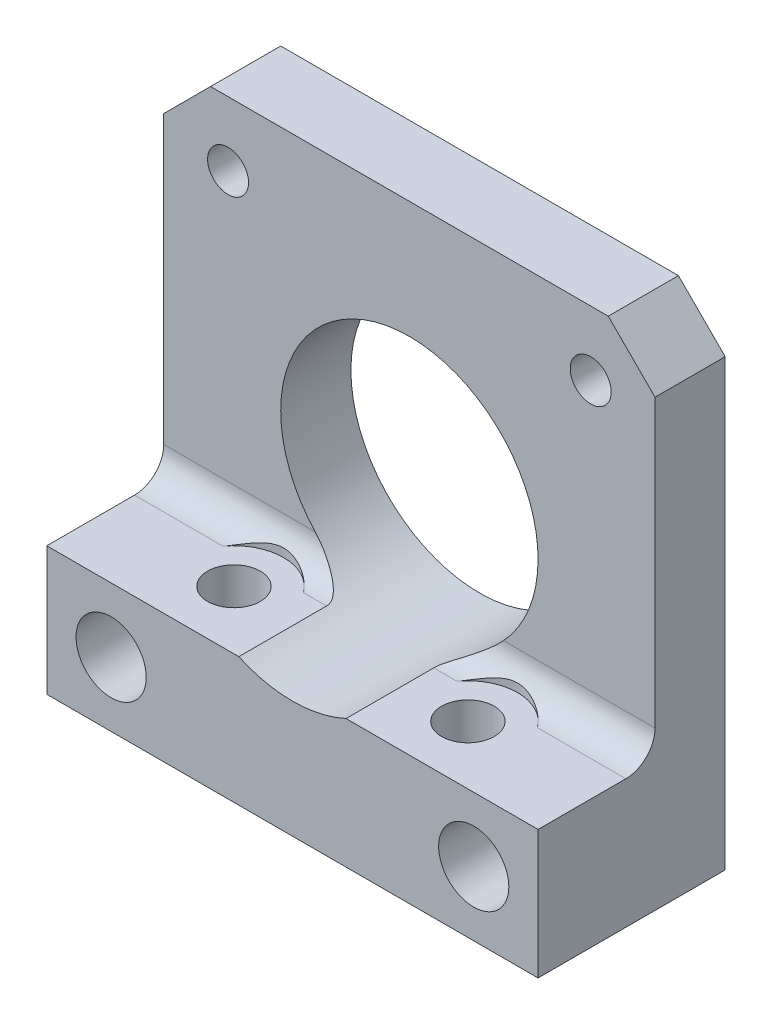
SolidWorks part; units mm, degrees
ref_plane "Plano frontal" through (0, 0, 0) normal (0, 0, 1) x (1, 0, 0)
ref_plane "Plano superior" through (0, 0, 0) normal (0, 1, 0) x (1, 0, 0)
ref_plane "Plano direito" through (0, 0, 0) normal (1, 0, 0) x (0, 0, -1)
sketch "Esboço1" plane through (0, 0, 0) normal (0, 0, 1) x (1, 0, 0)
  line L5 (21, 21) -> (-21, 21)
  line L6 (21, 21) -> (21, -21)
  line L7 (21, -21) -> (-21, -21)
  line L12 (-21, 21) -> (-21, -21)
  line L13 (21, 21) -> (-21, -21) construction
  line L14 (21, -21) -> (-21, 21) construction
  point P0 (0, 0)
  point P1 (0, 0)
  dimension "D1" = 42
  dimension "D2" = 42
extrude "Ressalto-extrusão3" add sketch "Esboço1" along normal blind 6
sketch "Esboço7" plane through (0, 0, 6) normal (0, 0, 1) x (1, 0, 0)
  line L0 (21, -21) -> (21, 21) construction
  line L1 (-21, -21) -> (21, -21)
  line L2 (-21, -21) -> (-21, -10)
  line L3 (-21, -10) -> (21, -10)
  line L4 (21, -21) -> (21, -10)
  dimension "D1" = 11
extrude "Ressalto-extrusão4" add sketch "Esboço7" along normal blind 10
sketch "Esboço6" plane through (0, 0, 0) normal (0, 0, -1) x (-1, 0, 0)
  line L0 (0, 21) -> (0, -21) construction
  line L1 (-21, 21) -> (21, 21) construction
  line L2 (21, -21) -> (-21, -21) construction
  line L4 (-15.5, 15.5) -> (15.5, 15.5) construction
  line L5 (-15.5, 15.5) -> (-15.5, -15.5) construction
  line L6 (-15.5, -15.5) -> (15.5, -15.5) construction
  line L7 (15.5, 15.5) -> (15.5, -15.5) construction
  line L8 (-15.5, 15.5) -> (15.5, -15.5) construction
  line L9 (-15.5, -15.5) -> (15.5, 15.5) construction
  circle A0 centre (0, 0) radius 11
  circle A1 centre (-15.5, 15.5) radius 1.75
  circle A2 centre (15.5, 15.5) radius 1.75
  circle A3 centre (15.5, -15.5) radius 1.75
  circle A4 centre (-15.5, -15.5) radius 1.75
  dimension "D1" = 22
  dimension "D3" = 3.5
  dimension "D2" = 31
extrude "Corte-extrusão3" cut sketch "Esboço6" against normal up to surface (16 mm away) up to face at (0, -15.5, 16)
chamfer "Chanfro1" distance 4 angle 45 2 edges at (-21, 21, 3) (21, 21, 3)
fillet "Filete1" radius 2.5 2 edges at (-12.7913, -10, 6) (12.7913, -10, 6)
sketch "Esboço8" plane through (0, -21, 0) normal (0, -1, 0) x (1, 0, 0)
  line L0 (0, 16) -> (0, 6) construction
  line L1 (-21, 16) -> (21, 16) construction
  line L2 (-13.75, 6) -> (-17.25, 6) construction
  line L3 (-10, 11) -> (10, 11) construction
  circle A0 centre (-10, 11) radius 2.25
  circle A1 centre (10, 11) radius 2.25
  point P11 (0, 11)
  dimension "D2" = 4.5
  dimension "D1" = 20
extrude "Corte-extrusão4" cut sketch "Esboço8" against normal up to surface (11 mm away) up to face at (-12.7913, -10, 12.25)
sketch "Esboço9" plane through (0, 0, 16) normal (0, 0, 1) x (1, 0, 0)
  circle A0 centre (-15.5, -15.5) radius 3
  circle A1 centre (15.5, -15.5) radius 3
  dimension "D1" = 6
extrude "Corte-extrusão5" cut sketch "Esboço9" against normal up to surface (10 mm away) up to face at (-17.25, 15.5, 6)
ref_plane "Plano1" through (0, 0, 0) normal (1, 0, 0) x (0, 0, -1)
sketch "Esboço10" plane through (0, -10, 0) normal (0, 1, 0) x (1, 0, 0)
  circle A0 centre (10, -11) radius 4.25
  circle A1 centre (-10, -11) radius 4.25
  dimension "D1" = 8.5
extrude "Corte-extrusão6" cut sketch "Esboço10" along normal up to surface up to face at (-13.3591, -9.1257, 7.153)
